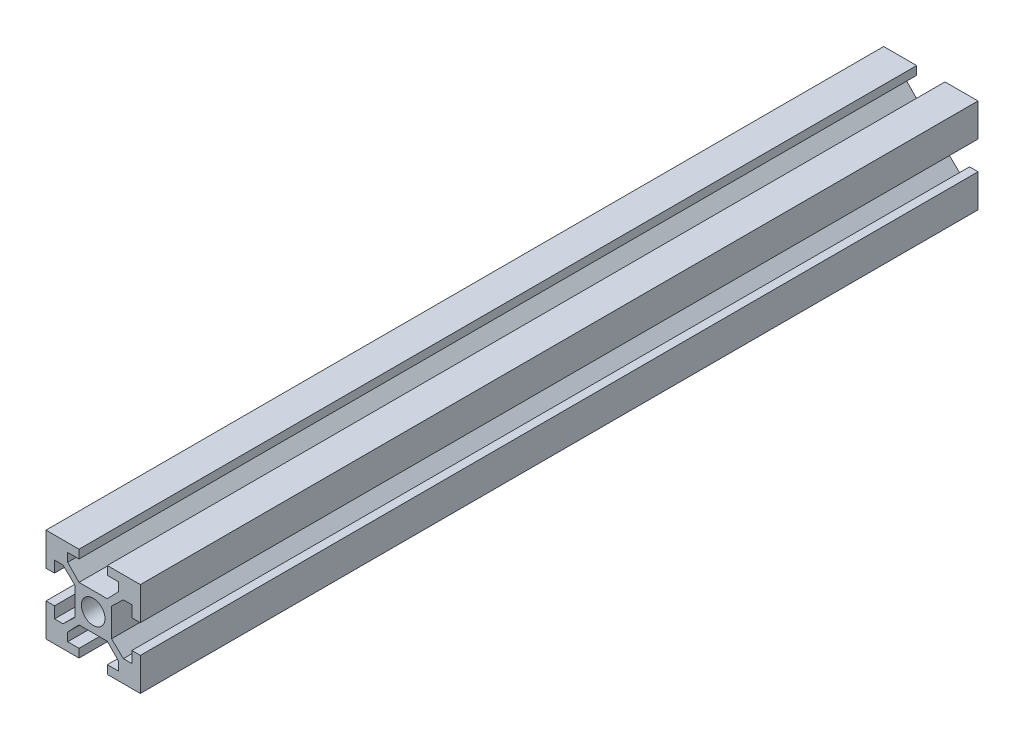
SolidWorks part; units mm, degrees
ref_plane "Front Plane" through (0, 0, 0) normal (0, 0, 1) x (1, 0, 0)
ref_plane "Top Plane" through (0, 0, 0) normal (0, 1, 0) x (1, 0, 0)
ref_plane "Right Plane" through (0, 0, 0) normal (1, 0, 0) x (0, 0, -1)
sketch "Sketch1" plane through (0, 0, 0) normal (0, 0, 1) x (1, 0, 0)
  line L0 (7, 0) -> (13, 0)
  line L1 (0, 0) -> (20, 0)
  line L2 (0, 0) -> (0, -20)
  line L3 (0, -20) -> (20, -20)
  line L4 (20, 0) -> (20, -20)
  line L5 (13, 0) -> (13, -1.8)
  line L6 (13, -1.8) -> (15.4, -1.8)
  line L7 (15.4, -1.8) -> (15.4, -3.6)
  line L8 (20, -13) -> (18.2, -13)
  line L9 (7, -6.1) -> (13, -6.1)
  line L10 (13, -6.1) -> (15.4, -3.6)
  line L18 (20, -6.6) -> (20, -12.6)
  line L46 (13.9, -6.6) -> (13.9, -12.6) [skipped]
  line L48 (20, -12.6) -> (18.2, -12.6) [skipped]
  line L49 (18.2, -12.6) -> (18.2, -15) [skipped]
  line L50 (18.2, -15) -> (16.4, -15) [skipped]
  line L51 (13.9, -12.6) -> (16.4, -15) [skipped]
  line L54 (13.4, -13.5) -> (7.4, -13.5) [skipped]
  line L55 (7.4, -17.8) -> (5, -17.8) [skipped]
  line L56 (5, -17.8) -> (5, -16) [skipped]
  line L57 (7.4, -13.5) -> (5, -16) [skipped]
  line L58 (7.4, -19.6) -> (7.4, -17.8) [skipped]
  line L61 (6.5, -13) -> (6.5, -7) [skipped]
  line L62 (6.5, -7) -> (4, -4.6) [skipped]
  line L63 (2.2, -4.6) -> (4, -4.6) [skipped]
  line L64 (2.2, -7) -> (2.2, -4.6) [skipped]
  line L65 (0.4, -7) -> (2.2, -7) [skipped]
  line L66 (7, -6.1) -> (4.6, -3.6)
  line L67 (4.6, -1.8) -> (4.6, -3.6)
  line L68 (7, -1.8) -> (4.6, -1.8)
  line L69 (7, 0) -> (7, -1.8)
  line L91 (18.2, -13) -> (18.2, -15.4)
  line L92 (18.2, -15.4) -> (16.4, -15.4)
  line L93 (13.9, -13) -> (16.4, -15.4)
  line L94 (13.9, -7) -> (13.9, -13)
  line L95 (13.9, -7) -> (16.4, -4.6)
  line L96 (18.2, -4.6) -> (16.4, -4.6)
  line L97 (18.2, -7) -> (18.2, -4.6)
  line L98 (20, -7) -> (18.2, -7)
  line L99 (20, -7) -> (20, -13)
  line L100 (13.4, -19.6) -> (7.4, -19.6) [skipped]
  line L101 (7, -20) -> (7, -18.2)
  line L102 (7, -18.2) -> (4.6, -18.2)
  line L103 (4.6, -18.2) -> (4.6, -16.4)
  line L104 (7, -13.9) -> (4.6, -16.4)
  line L105 (13, -13.9) -> (7, -13.9)
  line L106 (13, -13.9) -> (15.4, -16.4)
  line L107 (15.4, -18.2) -> (15.4, -16.4)
  line L108 (13, -18.2) -> (15.4, -18.2)
  line L109 (13, -20) -> (13, -18.2)
  line L110 (13, -20) -> (7, -20)
  line L111 (0, -7) -> (1.8, -7)
  line L112 (1.8, -7) -> (1.8, -4.6)
  line L113 (0.4, -13) -> (0.4, -7) [skipped]
  line L114 (1.8, -4.6) -> (3.6, -4.6)
  line L115 (6.1, -7) -> (3.6, -4.6)
  line L116 (6.1, -13) -> (6.1, -7)
  line L117 (6.1, -13) -> (3.6, -15.4)
  line L118 (1.8, -15.4) -> (3.6, -15.4)
  line L119 (1.8, -13) -> (1.8, -15.4)
  line L120 (0, -13) -> (1.8, -13)
  line L121 (0, -13) -> (0, -7)
  circle A1 centre (10, -10) radius 2.5
  point P8 (10, 0)
  point P18 (10, -6.1)
  point P54 (10, -10)
  dimension "D7" = 5
  dimension "D8" = 4
  dimension "D1" = 20
  dimension "D2" = 20
  dimension "D3" = 6
  dimension "D4" = 1.8
  dimension "D5" = 2.4
  dimension "D6" = 1.8
  dimension "D9" = 3.9
  dimension "D12" = 7
  dimension "D13" = 3.9
  dimension "D11" = 3.9
  dimension "D10" = 4
extrude "Boss-Extrude1" add sketch "Sketch1" along normal blind 177.6 contours L120 L2 L3 L101 L102 L103 L104 L105 L106 L107 L108 L109 L4 L8 L91 L92 L93 L94 L95 L96 L97 L98 L1 L5 L6 L7 L10 L9 L66 L67 L68 L69 L111 L112 L114 L115 L116 L117 L118 L119 A1
